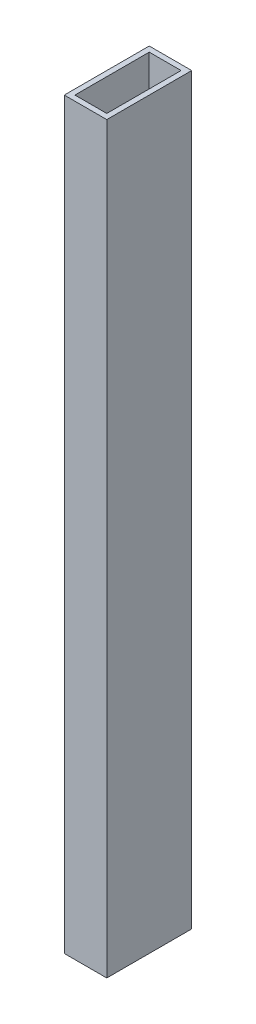
SolidWorks part; units mm, degrees
ref_plane "Front Plane" through (0, 0, 0) normal (0, 0, 1) x (1, 0, 0)
ref_plane "Top Plane" through (0, 0, 0) normal (0, 1, 0) x (1, 0, 0)
ref_plane "Right Plane" through (0, 0, 0) normal (1, 0, 0) x (0, 0, -1)
sketch "Sketch1" plane through (0, 0, 0) normal (0, 1, 0) x (1, 0, 0)
  line L1 (0, 0) -> (25.4, 0)
  line L2 (0, 0) -> (0, 50.8)
  line L3 (0, 50.8) -> (25.4, 50.8)
  line L4 (25.4, 0) -> (25.4, 50.8)
  line L5 (3.175, 47.625) -> (22.225, 47.625)
  line L6 (3.175, 47.625) -> (3.175, 3.175)
  line L7 (3.175, 3.175) -> (22.225, 3.175)
  line L8 (22.225, 47.625) -> (22.225, 3.175)
  dimension "D1" = 25.4
  dimension "D2" = 50.8
  dimension "D3" = 3.175
  dimension "D4" = 3.175
  dimension "D5" = 3.175
  dimension "D6" = 3.175
extrude "Boss-Extrude1" add sketch "Sketch1" along normal blind 444.5
